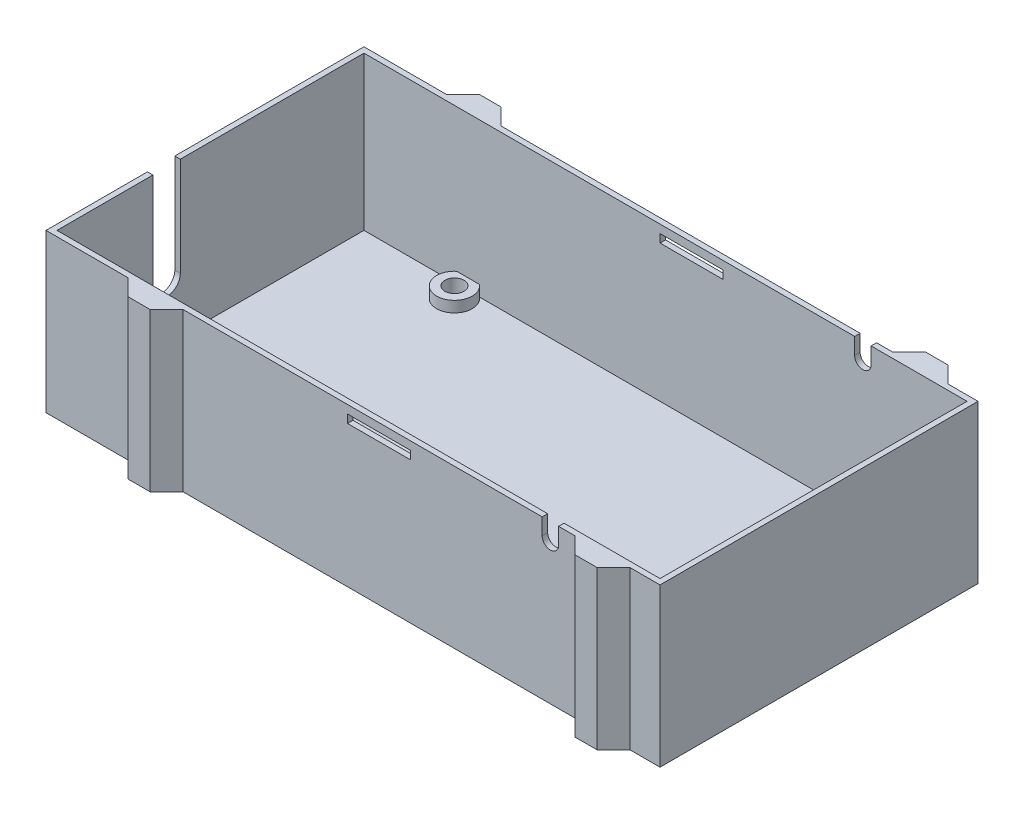
SolidWorks part; units mm, degrees
ref_plane "Front Plane" through (0, 0, 0) normal (0, 0, 1) x (1, 0, 0)
ref_plane "Top Plane" through (0, 0, 0) normal (0, 1, 0) x (1, 0, 0)
ref_plane "Right Plane" through (0, 0, 0) normal (1, 0, 0) x (0, 0, -1)
sketch "Sketch1" plane through (0, 0, 0) normal (0, 1, 0) x (1, 0, 0)
  line L1 (-56, 29) -> (56, 29)
  line L2 (-56, 29) -> (-56, -29)
  line L3 (-56, -29) -> (56, -29)
  line L4 (56, 29) -> (56, -29)
  line L5 (-56, 29) -> (56, -29) construction
  line L6 (-56, -29) -> (56, 29) construction
  point P0 (0, 0)
  dimension "D1" = 112
  dimension "D2" = 58
extrude "Boss-Extrude1" add sketch "Sketch1" along normal blind 0.8
sketch "Sketch2" plane through (0, 0.8, 0) normal (0, 1, 0) x (1, 0, 0)
  line L1 (-56, 29) -> (56, 29)
  line L2 (-56, 29) -> (-56, -29)
  line L3 (-56, -29) -> (56, -29)
  line L4 (56, 29) -> (56, -29)
  line L5 (-56, 29) -> (56, -29) construction
  line L6 (-56, -29) -> (56, 29) construction
  line L7 (-55, 28) -> (55, 28)
  line L8 (-55, 28) -> (-55, -28)
  line L9 (-55, -28) -> (55, -28)
  line L10 (55, 28) -> (55, -28)
  line L11 (-55, 28) -> (55, -28) construction
  line L12 (-55, -28) -> (55, 28) construction
  point P0 (0, 0)
  point P7 (0, 0)
  dimension "D1" = 1
  dimension "D2" = 1
extrude "Boss-Extrude2" add sketch "Sketch2" along normal blind 28
sketch "Sketch3" plane through (0, 0.8, 0) normal (0, 1, 0) x (1, 0, 0)
  line L0 (55, 28) -> (-55, 28) construction
  line L1 (-55, -28) -> (55, -28) construction
  line L3 (-55, -28) -> (55, -28) construction
  line L4 (55, -28) -> (55, 28) construction
  circle A0 centre (-36, 25.5) radius 1.75
  circle A1 centre (-36, -25.5) radius 1.75
  circle A2 centre (45.5, 25.5) radius 1.75
  circle A3 centre (45.5, -25.5) radius 1.75
  dimension "D1" = 2.5
  dimension "D2" = 3.5
  dimension "D3" = 3.5
  dimension "D4" = 2.5
  dimension "D5" = 81.5
  dimension "D6" = 81.5
  dimension "D7" = 3.5
  dimension "D8" = 3.5
  dimension "D9" = 2.5
  dimension "D10" = 2.5
  dimension "D11" = 9.5
  dimension "D12" = 9.5
extrude "Cut-Extrude1" cut sketch "Sketch3" against normal blind 28
sketch "Sketch4" plane through (0, 0.8, 0) normal (0, 1, 0) x (1, 0, 0)
  circle A0 centre (-36, 25.5) radius 3.25
  circle A1 centre (45.5, 25.5) radius 3.25
  circle A2 centre (-36, -25.5) radius 3.25
  circle A3 centre (45.5, -25.5) radius 3.25
  circle A4 centre (-36, 25.5) radius 1.75 construction
  circle A5 centre (45.5, 25.5) radius 1.75 construction
  circle A6 centre (-36, -25.5) radius 1.75 construction
  circle A7 centre (45.5, -25.5) radius 1.75 construction
  circle A8 centre (-36, 25.5) radius 1.75
  circle A9 centre (45.5, 25.5) radius 1.75
  circle A10 centre (45.5, -25.5) radius 1.75
  circle A11 centre (-36, -25.5) radius 1.75
  dimension "D1" = 1.5
  dimension "D2" = 1.5
  dimension "D3" = 1.5
  dimension "D4" = 1.5
extrude "Boss-Extrude3" add sketch "Sketch4" along normal blind 2
sketch "Sketch5" plane through (-55, 0, 0) normal (1, 0, 0) x (0, 0, -1)
  line L0 (28, 0.8) -> (-28, 0.8) construction
  line L1 (-28, 28.8) -> (-28, 0.8) construction
  line L2 (28, 28.8) -> (-28, 28.8) construction
  line L4 (-10.5, 10.8) -> (-10.5, 28.8)
  line L5 (-10.5, 28.8) -> (-5.5, 28.8)
  line L6 (-5.5, 10.8) -> (-5.5, 28.8)
  arc A0 (-10.5, 10.8) -> (-5.5, 10.8) centre (-8, 10.8) ccw
  dimension "D1" = 5
  dimension "D2" = 10
  dimension "D3" = 20
  dimension "D4" = 2.5
extrude "Cut-Extrude2" cut sketch "Sketch5" against normal blind 2
sketch "Sketch6" plane through (0, 0, 29) normal (0, 0, 1) x (1, 0, 0)
  line L0 (-56, 28.8) -> (56, 28.8) construction
  line L1 (56, 28.8) -> (56, 0) construction
  line L4 (34.5, 25.8) -> (34.5, 28.8)
  line L5 (34.5, 28.8) -> (37.5, 28.8)
  line L6 (37.5, 25.8) -> (37.5, 28.8)
  arc A0 (34.5, 25.8) -> (37.5, 25.8) centre (36, 25.8) ccw
  dimension "D1" = 3
  dimension "D2" = 3
  dimension "D3" = 20
extrude "Cut-Extrude3" cut sketch "Sketch6" against normal blind 72
sketch "Sketch7" plane through (0, 0, 0) normal (0, -1, 0) x (1, 0, 0)
  line L0 (-41, 29) -> (-38, 32)
  line L1 (-56, 29) -> (56, 29) construction
  line L2 (-38, 32) -> (-34, 32)
  line L3 (-34, 32) -> (-31, 29)
  line L4 (-31, 29) -> (-41, 29)
  line L5 (40.5, 29) -> (43.5, 32)
  line L6 (43.5, 32) -> (47.5, 32)
  line L7 (47.5, 32) -> (50.5, 29)
  line L8 (50.5, 29) -> (40.5, 29)
  line L9 (-41, -29) -> (-38, -32)
  line L10 (56, -29) -> (-56, -29) construction
  line L11 (-38, -32) -> (-34, -32)
  line L12 (-34, -32) -> (-31, -29)
  line L13 (-31, -29) -> (-41, -29)
  line L14 (40.5, -29) -> (43.5, -32)
  line L15 (43.5, -32) -> (47.5, -32)
  line L16 (47.5, -32) -> (50.5, -29)
  line L17 (50.5, -29) -> (40.5, -29)
  circle A0 centre (-36, 25.5) radius 1.75 construction
  circle A1 centre (45.5, 25.5) radius 1.75 construction
  circle A2 centre (-36, -25.5) radius 1.75 construction
  dimension "D1" = 5
  dimension "D2" = 5
  dimension "D3" = 3
  dimension "D4" = 45
  dimension "D5" = 5
  dimension "D6" = 5
  dimension "D7" = 5
  dimension "D8" = 5
  dimension "D9" = 3
  dimension "D10" = 45
extrude "Boss-Extrude4" add sketch "Sketch7" against normal blind 28.8
sketch "Sketch8" plane through (0, 0, 29) normal (0, 0, 1) x (1, 0, 0)
  line L0 (-31, 28.8) -> (34.5, 28.8) construction
  line L1 (-1, 27.3) -> (10.5, 27.3)
  line L2 (-1, 27.3) -> (-1, 25.8)
  line L3 (-1, 25.8) -> (10.5, 25.8)
  line L4 (10.5, 27.3) -> (10.5, 25.8)
  line L5 (-1, 27.3) -> (10.5, 25.8) construction
  line L6 (-1, 25.8) -> (10.5, 27.3) construction
  line L7 (-31, 28.8) -> (-31, 0) construction
  line L8 (40.5, 28.8) -> (40.5, 0) construction
  point P0 (4.75, 26.55)
  dimension "D1" = 1.5
  dimension "D2" = 1.5
  dimension "D3" = 30
  dimension "D4" = 30
extrude "Cut-Extrude4" cut sketch "Sketch8" against normal blind 70
